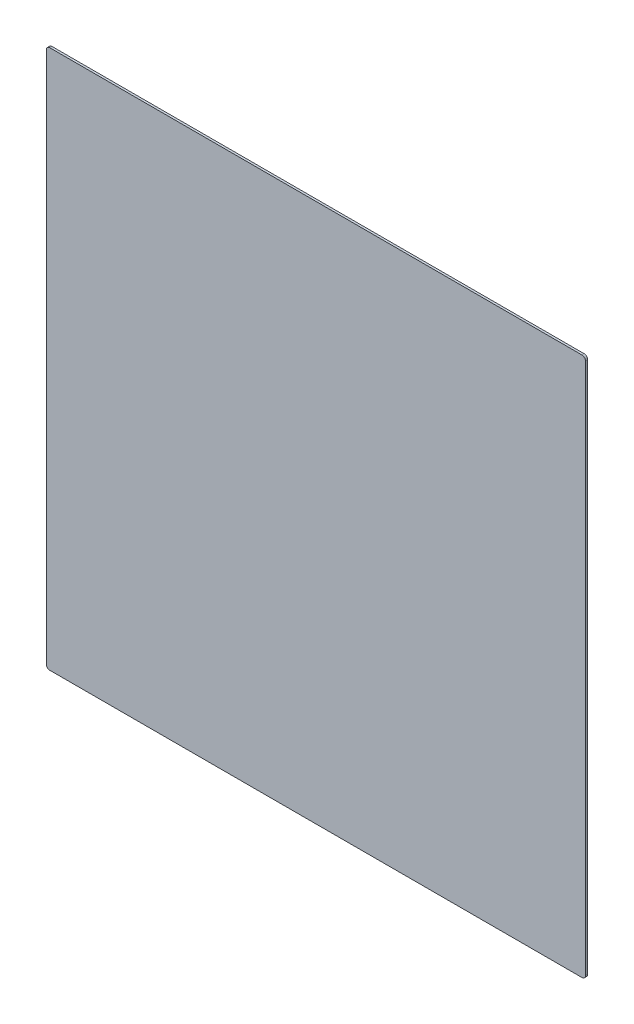
SolidWorks part; units mm, degrees
material "ABS"
ref_plane "Top Plane" through (0, 0, 0) normal (0, 0, 1) x (1, 0, 0)
ref_plane "Front Plane" through (0, 0, 0) normal (0, 1, 0) x (1, 0, 0)
ref_plane "Right Plane" through (0, 0, 0) normal (1, 0, 0) x (0, 0, -1)
sketch "Sketch1" plane through (0, 0, 0) normal (0, 0, 1) x (1, 0, 0)
  line L1 (-152.5, 152.5) -> (152.5, 152.5)
  line L2 (-152.5, 152.5) -> (-152.5, -152.5)
  line L3 (-152.5, -152.5) -> (152.5, -152.5)
  line L4 (152.5, 152.5) -> (152.5, -152.5)
  line L5 (-152.5, 152.5) -> (152.5, -152.5) construction
  line L6 (-152.5, -152.5) -> (152.5, 152.5) construction
  point P0 (0, 0)
  dimension "D1" = 305
  dimension "D2" = 305
extrude "Boss-Extrude1" add sketch "Sketch1" along normal blind 1.25
fillet "Fillet1" radius 2 4 edges at (-152.5, -152.5, 0.625) (152.5, -152.5, 0.625) (-152.5, 152.5, 0.625) (152.5, 152.5, 0.625)
